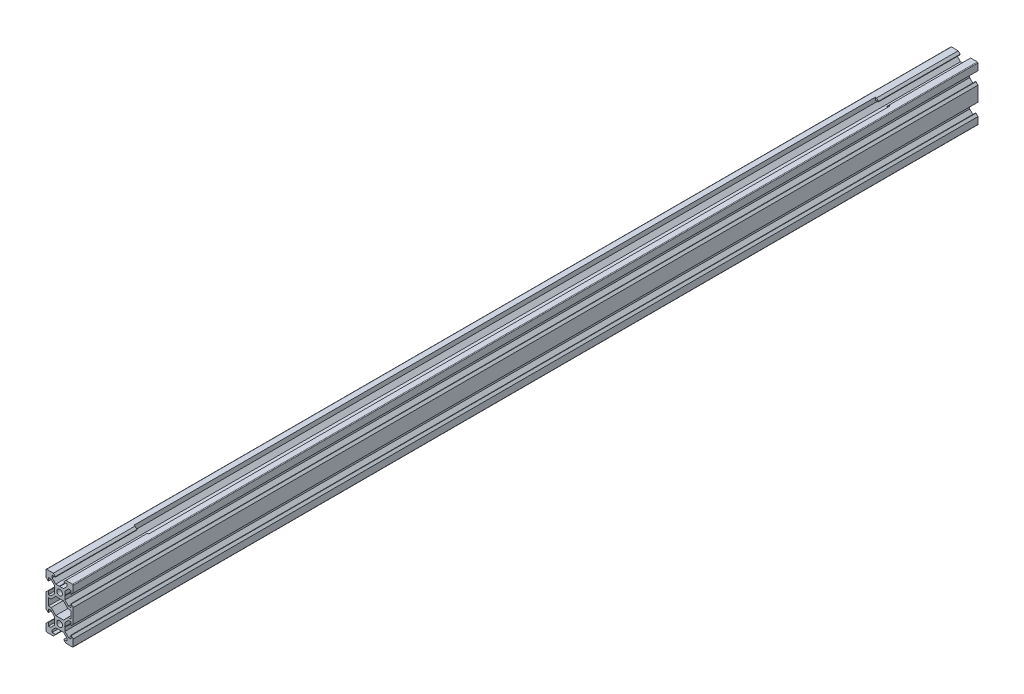
SolidWorks part; units mm, degrees
material "6061-T6 (SS)"
ref_plane "Front Plane" through (0, 0, 0) normal (0, 0, 1) x (1, 0, 0)
ref_plane "Top Plane" through (0, 0, 0) normal (0, 1, 0) x (1, 0, 0)
ref_plane "Right Plane" through (0, 0, 0) normal (1, 0, 0) x (0, 0, -1)
sketch "Sketch1" plane through (0, 0, 0) normal (0, 0, 1) x (1, 0, 0)
  line L0 (0, 0) -> (10, 0) construction
  line L1 (9.5, -20) -> (-9.5, -20)
  line L2 (10, -19.5) -> (10, 19.5)
  line L3 (9.5, 20) -> (-9.5, 20)
  line L4 (-10, -19.5) -> (-10, 19.5)
  line L5 (10, -20) -> (-10, 20) construction
  line L6 (10, 20) -> (-10, -20) construction
  circle A0 centre (0, 10) radius 2.1
  circle A1 centre (0, -10) radius 2.1
  arc A2 (-9.5, -20) -> (-10, -19.5) centre (-9.5, -19.5) cw
  arc A3 (9.5, -20) -> (10, -19.5) centre (9.5, -19.5) ccw
  arc A4 (10, 19.5) -> (9.5, 20) centre (9.5, 19.5) ccw
  arc A5 (-9.5, 20) -> (-10, 19.5) centre (-9.5, 19.5) ccw
  point P0 (0, 0)
  line B0 (0, 10) -> (0, 20) construction
  line B1 (0, 13.69) -> (-0.21, 13.9)
  line B2 (-0.21, 13.9) -> (-2.8393, 13.9)
  line B3 (-2.8393, 13.9) -> (-5.5, 16.5607)
  line B4 (-5.5, 16.5607) -> (-5.5, 18.2)
  line B5 (-5.5, 18.2) -> (-3.125, 18.2)
  line B6 (-3.125, 18.2) -> (-3.125, 18.545)
  line B7 (-3.125, 18.545) -> (-4.58, 20)
  line B8 (-4.58, 20) -> (4.58, 20)
  line B9 (0, 10) -> (-5.9132, 15.9132) construction
  line B10 (3.125, 18.545) -> (4.58, 20)
  line B11 (3.125, 18.2) -> (3.125, 18.545)
  line B12 (5.5, 18.2) -> (3.125, 18.2)
  line B13 (5.5, 16.5607) -> (5.5, 18.2)
  line B14 (2.8393, 13.9) -> (5.5, 16.5607)
  line B15 (0.21, 13.9) -> (2.8393, 13.9)
  line B16 (0, 13.69) -> (0.21, 13.9)
  line B17 (0, 10) -> (-10, 10) construction
  line B18 (-3.69, 10) -> (-3.9, 9.79)
  line B19 (-3.9, 9.79) -> (-3.9, 7.1607)
  line B20 (-3.9, 7.1607) -> (-6.5607, 4.5)
  line B21 (-6.5607, 4.5) -> (-8.2, 4.5)
  line B22 (-8.2, 4.5) -> (-8.2, 6.875)
  line B23 (-8.2, 6.875) -> (-8.545, 6.875)
  line B24 (-8.545, 6.875) -> (-10, 5.42)
  line B25 (-10, 5.42) -> (-10, 14.58)
  line B26 (0, 10) -> (-5.9132, 4.0868) construction
  line B27 (-8.545, 13.125) -> (-10, 14.58)
  line B28 (-8.2, 13.125) -> (-8.545, 13.125)
  line B29 (-8.2, 15.5) -> (-8.2, 13.125)
  line B30 (-6.5607, 15.5) -> (-8.2, 15.5)
  line B31 (-3.9, 12.8393) -> (-6.5607, 15.5)
  line B32 (-3.9, 10.21) -> (-3.9, 12.8393)
  line B33 (-3.69, 10) -> (-3.9, 10.21)
  line B34 (0, -10) -> (-10, -10) construction
  line B35 (-3.69, -10) -> (-3.9, -10.21)
  line B36 (-3.9, -10.21) -> (-3.9, -12.8393)
  line B37 (-3.9, -12.8393) -> (-6.5607, -15.5)
  line B38 (-6.5607, -15.5) -> (-8.2, -15.5)
  line B39 (-8.2, -15.5) -> (-8.2, -13.125)
  line B40 (-8.2, -13.125) -> (-8.545, -13.125)
  line B41 (-8.545, -13.125) -> (-10, -14.58)
  line B42 (-10, -14.58) -> (-10, -5.42)
  line B43 (0, -10) -> (-5.9132, -15.9132) construction
  line B44 (-8.545, -6.875) -> (-10, -5.42)
  line B45 (-8.2, -6.875) -> (-8.545, -6.875)
  line B46 (-8.2, -4.5) -> (-8.2, -6.875)
  line B47 (-6.5607, -4.5) -> (-8.2, -4.5)
  line B48 (-3.9, -7.1607) -> (-6.5607, -4.5)
  line B49 (-3.9, -9.79) -> (-3.9, -7.1607)
  line B50 (-3.69, -10) -> (-3.9, -9.79)
  line B51 (0, -10) -> (0, -20) construction
  line B52 (0, -13.69) -> (0.21, -13.9)
  line B53 (0.21, -13.9) -> (2.8393, -13.9)
  line B54 (2.8393, -13.9) -> (5.5, -16.5607)
  line B55 (5.5, -16.5607) -> (5.5, -18.2)
  line B56 (5.5, -18.2) -> (3.125, -18.2)
  line B57 (3.125, -18.2) -> (3.125, -18.545)
  line B58 (3.125, -18.545) -> (4.58, -20)
  line B59 (4.58, -20) -> (-4.58, -20)
  line B60 (0, -10) -> (5.9132, -15.9132) construction
  line B61 (-3.125, -18.545) -> (-4.58, -20)
  line B62 (-3.125, -18.2) -> (-3.125, -18.545)
  line B63 (-5.5, -18.2) -> (-3.125, -18.2)
  line B64 (-5.5, -16.5607) -> (-5.5, -18.2)
  line B65 (-2.8393, -13.9) -> (-5.5, -16.5607)
  line B66 (-0.21, -13.9) -> (-2.8393, -13.9)
  line B67 (0, -13.69) -> (-0.21, -13.9)
  line B68 (0, -10) -> (10, -10) construction
  line B69 (3.69, -10) -> (3.9, -9.79)
  line B70 (3.9, -9.79) -> (3.9, -7.1607)
  line B71 (3.9, -7.1607) -> (6.5607, -4.5)
  line B72 (6.5607, -4.5) -> (8.2, -4.5)
  line B73 (8.2, -4.5) -> (8.2, -6.875)
  line B74 (8.2, -6.875) -> (8.545, -6.875)
  line B75 (8.545, -6.875) -> (10, -5.42)
  line B76 (10, -5.42) -> (10, -14.58)
  line B77 (0, -10) -> (5.9132, -4.0868) construction
  line B78 (8.545, -13.125) -> (10, -14.58)
  line B79 (8.2, -13.125) -> (8.545, -13.125)
  line B80 (8.2, -15.5) -> (8.2, -13.125)
  line B81 (6.5607, -15.5) -> (8.2, -15.5)
  line B82 (3.9, -12.8393) -> (6.5607, -15.5)
  line B83 (3.9, -10.21) -> (3.9, -12.8393)
  line B84 (3.69, -10) -> (3.9, -10.21)
  line B85 (0, 10) -> (10, 10) construction
  line B86 (3.69, 10) -> (3.9, 10.21)
  line B87 (3.9, 10.21) -> (3.9, 12.8393)
  line B88 (3.9, 12.8393) -> (6.5607, 15.5)
  line B89 (6.5607, 15.5) -> (8.2, 15.5)
  line B90 (8.2, 15.5) -> (8.2, 13.125)
  line B91 (8.2, 13.125) -> (8.545, 13.125)
  line B92 (8.545, 13.125) -> (10, 14.58)
  line B93 (10, 14.58) -> (10, 5.42)
  line B94 (0, 10) -> (5.9132, 15.9132) construction
  line B95 (8.545, 6.875) -> (10, 5.42)
  line B96 (8.2, 6.875) -> (8.545, 6.875)
  line B97 (8.2, 4.5) -> (8.2, 6.875)
  line B98 (6.5607, 4.5) -> (8.2, 4.5)
  line B99 (3.9, 7.1607) -> (6.5607, 4.5)
  line B100 (3.9, 9.79) -> (3.9, 7.1607)
  line B101 (3.69, 10) -> (3.9, 9.79)
  line B102 (-8.2, -2.7) -> (-8.2, 2.7)
  line B103 (-8.2, 2.7) -> (-6.2393, 2.7)
  line B104 (-6.2393, 2.7) -> (-2.8393, 6.1)
  line B105 (-2.8393, 6.1) -> (2.8393, 6.1)
  line B106 (0, 6.1) -> (0, 0) construction
  line B107 (0, 0) -> (-8.2, 0) construction
  line B108 (6.2393, 2.7) -> (2.8393, 6.1)
  line B109 (8.2, 2.7) -> (6.2393, 2.7)
  line B110 (8.2, -2.7) -> (8.2, 2.7)
  line B111 (8.2, -2.7) -> (6.2393, -2.7)
  line B112 (6.2393, -2.7) -> (2.8393, -6.1)
  line B113 (-2.8393, -6.1) -> (2.8393, -6.1)
  line B114 (-6.2393, -2.7) -> (-2.8393, -6.1)
  line B115 (-8.2, -2.7) -> (-6.2393, -2.7)
  line B116 (0, 6.1) -> (0, 10) construction
  line B117 (0, 10) -> (-5.0927, 4.9073) construction
  dimension "D4" = 4.2
  dimension "D5" = 0.5
  dimension "D1" = 20
  dimension "D2" = 40
  dimension "D3" = 20
sketch_block_instance "V Slot 1-4"
sketch_block "V Slot 1" parameters "D1"=10, "D2"=11, "D3"=4.3, "D4"=1.8, "D5"=0.21, "D6"=45, "D7"=9.16, "D8"=1.5, "D9"=6.25
sketch_block_instance "V Slot 1-5"
sketch_block_instance "V Slot 1-6"
sketch_block_instance "V Slot 1-7"
sketch_block_instance "V Slot 1-8"
sketch_block_instance "V Slot 1-9"
sketch_block_instance "Center Cutout 1-1"
sketch_block "Center Cutout 1" parameters "D1"=5.4, "D2"=12.2, "D3"=8.2, "D4"=45, "D5"=10, "D6"=1.5
extrude "Boss-Extrude1" add sketch "Sketch1" along normal mid plane 665 contours B101 B86 B87 B88 B89 B90 B91 B92 L2 A4 L3 B10 B11 B12 B13 B14 B15 B16 B1 B2 B3 B4 B5 B6 B7 A5 L4 B27 B28 B29 B30 B31 B32 B33 B18 B19 B20 B21 B22 B23 B24 B44 B45 B46 B47 B48 B49 B50 B35
sketch "Sketch2" plane through (0, 0, 0) normal (0, 0, 1) x (1, 0, 0)
  line L0 (5.5, -20) -> (5.5, -18.2)
  line L1 (5.5, -18.2) -> (-5.5, -18.2)
  line L2 (-5.5, -18.2) -> (-5.5, -20)
  line L3 (5.5, -20) -> (-5.5, -20)
  line L4 (-4.58, -20) -> (-9.5, -20) construction
  line L5 (5.5, -18.2) -> (3.125, -18.2) construction
  line L6 (5.5, -16.5607) -> (5.5, -18.2) construction
  line L7 (-5.5, -16.5607) -> (-5.5, -18.2) construction
extrude "Cut-Extrude1" cut sketch "Sketch2" along normal offset from surface 60 and the other way offset from surface (272.5 mm away) 60 up to face at (0, 0, 332.5) other way up to face at (0, 0, -332.5)
mirror "Mirror1" about plane through (0, 0, 0) normal (0, 1, 0) of "Cut-Extrude1"
